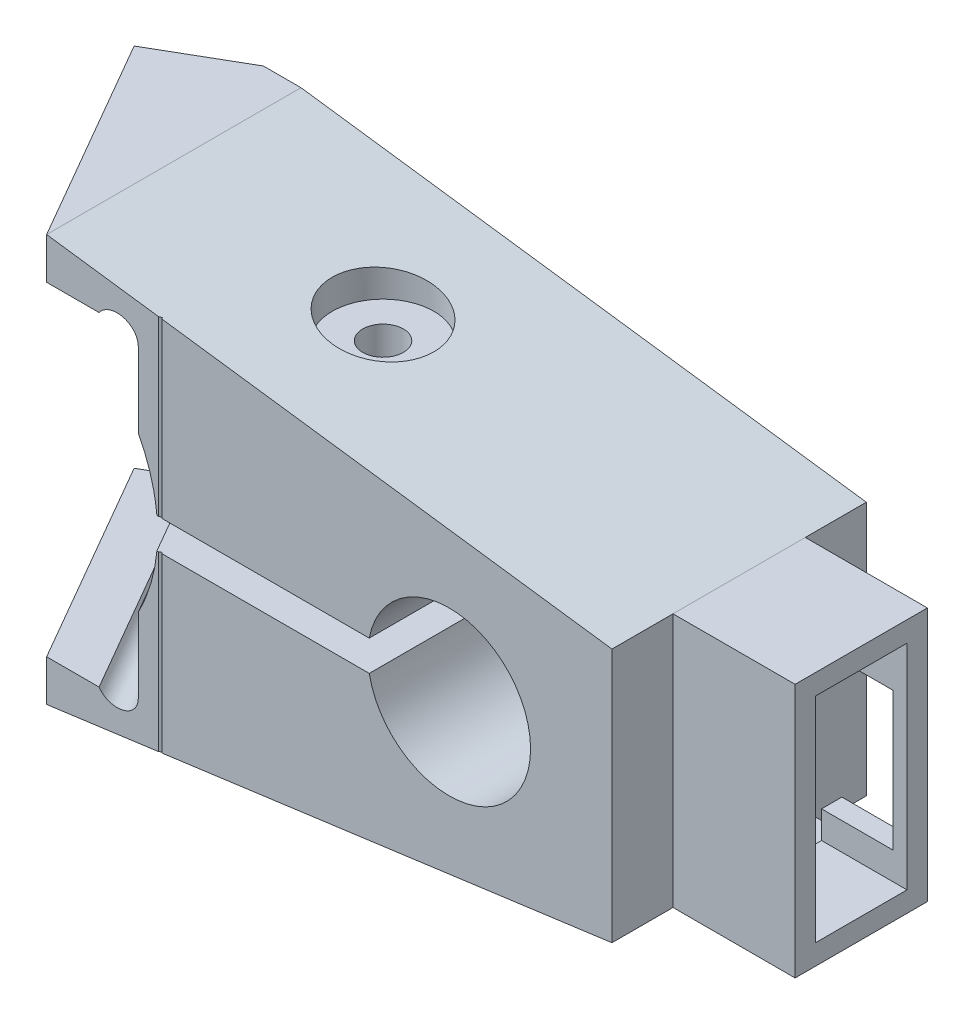
SolidWorks part; units mm, degrees
material "ABS"
ref_plane "Front Plane" through (0, 0, 0) normal (0, 0, 1) x (1, 0, 0)
ref_plane "Top Plane" through (0, 0, 0) normal (0, 1, 0) x (1, 0, 0)
ref_plane "Right Plane" through (0, 0, 0) normal (1, 0, 0) x (0, 0, -1)
sketch "Sketch1" plane through (0, 0, 0) normal (0, 1, 0) x (1, 0, 0)
  line L0 (-35, 12.5) -> (-20.5662, -12.5)
  line L1 (-20.5662, -12.5) -> (35, -12.5)
  line L2 (-27.7831, 0) -> (-41.077, -7.6752) construction
  line L3 (-35, 12.5) -> (35, 12.5)
  line L4 (35, -12.5) -> (35, 12.5)
  line L5 (-23.0337, -8.2263) -> (35, 12.5) construction
  line L6 (-35, 12.5) -> (35, -12.5) construction
  point P0 (0, 0)
  dimension "D1" = 70
  dimension "D2" = 25
  dimension "D3" = 120
extrude "Boss-Extrude1" add sketch "Sketch1" along normal blind 40
sketch "Sketch2" plane through (0, 0, 12.5) normal (0, 0, 1) x (1, 0, 0)
  line L0 (-20.5662, 40) -> (35, 32.5)
  line L1 (35, 40) -> (35, 0) construction
  line L3 (35, 7.5) -> (-20.5662, 0)
  line L4 (-20.5662, 0) -> (35, 0)
  line L5 (35, 0) -> (35, 7.5)
  line L6 (35, 32.5) -> (35, 40)
  line L7 (35, 40) -> (-20.5662, 40)
  dimension "D1" = 25
  dimension "D2" = 7.5
  dimension "D3" = 7.5
  dimension "D4" = 97.687
  dimension "D5" = 97.687
extrude "Cut-Extrude1" cut sketch "Sketch2" against normal blind 40
sketch "Sketch3" plane through (-20.8373, 0, 12.0304) normal (-0.866, 0, 0.5) x (0.5, 0, 0.866)
  line L1 (-12.8642, 25.3819) -> (-8.4874, 25.3819)
  line L2 (-12.8642, 25.3819) -> (-12.8642, 17.4606)
  line L3 (-12.8642, 17.4606) -> (-8.4874, 17.4606)
  line L4 (-8.4874, 25.3819) -> (-8.4874, 17.4606)
  line L5 (-12.8642, 25.3819) -> (-8.4874, 17.4606) construction
  line L6 (-12.8642, 17.4606) -> (-8.4874, 25.3819) construction
  point P0 (-10.6758, 21.4213)
extrude "Boss-Extrude2" add sketch "Sketch3" along normal blind 40
sketch "Sketch4" plane through (-4.2437, 0, -7.3503) normal (0.5, 0, 0.866) x (0.866, 0, -0.5)
  line L0 (-25.2609, 35.9341) -> (-19.5976, 35.9341)
  line L1 (-52.0609, 0.9968) -> (-14.0609, 0.9968) construction
  line L2 (-52.0609, 0.9968) -> (-52.0609, 38.9968) construction
  line L3 (-52.0609, 38.9968) -> (-14.0609, 38.9968) construction
  line L4 (-14.0609, 0.9968) -> (-14.0609, 38.9968) construction
  line L5 (-52.0609, 0.9968) -> (-20.0148, 33.0429) construction
  line L6 (-52.0609, 38.9968) -> (-14.0609, 0.9968) construction
  line L7 (-24.0609, 40) -> (-24.0609, 0) construction
  line L8 (-16.2609, 34.9968) -> (-16.2609, 27.6232)
  line L9 (-16.7881, 36.2696) -> (-14.0609, 38.9968) construction
  line L10 (-69.3542, 19.9968) -> (-7.4274, 19.9968) construction
  line L11 (-16.2609, 4.9968) -> (-16.2609, 12.3703)
  line L12 (-25.2609, 4.0594) -> (-19.5976, 4.0594)
  line L13 (-25.2609, 35.9341) -> (-25.2609, 26.6131)
  line L14 (-25.2609, 26.6131) -> (-69.3542, 27.5468)
  line L15 (-69.3542, 27.5468) -> (-69.3542, 11.5496)
  line L16 (-69.3542, 11.5496) -> (-25.2609, 11.5496)
  line L17 (-25.2609, 11.5496) -> (-25.2609, 4.0594)
  arc A0 (-16.2609, 34.9968) -> (-19.5976, 35.9341) centre (-18.0609, 34.9968) ccw
  arc A1 (-16.2609, 4.9968) -> (-19.5976, 4.0594) centre (-18.0609, 4.9968) cw
  arc A2 (-16.2609, 12.3703) -> (-16.2609, 27.6232) centre (-33.0609, 19.9968) ccw
  point P0 (-33.0609, 19.9968)
  dimension "D4" = 3.6
  dimension "D5" = 5.6633
  dimension "D8" = 36.9
  dimension "D1" = 38
  dimension "D2" = 38
  dimension "D3" = 10
  dimension "D6" = 4
  dimension "D7" = 9
extrude "Cut-Extrude2" cut sketch "Sketch4" against normal through all both and the other way through all
sketch "Sketch5" plane through (0, 0, -12.5) normal (0, 0, -1) x (-1, 0, 0)
  line L0 (-35, 32.5) -> (-35, 7.5) construction
  line L1 (35, 40) -> (20.5662, 40) construction
  line L2 (-11.1413, 21.5) -> (29.8749, 21.5)
  line L3 (29.8749, 21.5) -> (29.8749, 18.5)
  line L4 (29.8749, 18.5) -> (-11.1425, 18.5)
  arc A0 (-11.1413, 21.5) -> (-11.1425, 18.5) centre (-19, 20.0032) ccw
  point P1 (-35, 20)
  dimension "D1" = 16
  dimension "D2" = 16
  dimension "D3" = 3
  dimension "D4" = 1.5
  dimension "D5" = 18.5
  dimension "D6" = 18.5
extrude "Cut-Extrude3" cut sketch "Sketch5" against normal blind 40
sketch "Sketch6" plane through (0, 18.5, 0) normal (0, 1, 0) x (1, 0, 0)
  circle A0 centre (0, 0) radius 2
  dimension "D1" = 4
extrude "Cut-Extrude4" cut sketch "Sketch6" against normal through all both and the other way through all
sketch "Sketch7" plane through (0, 0, 0) normal (0, -1, 0) x (1, 0, 0)
  line L1 (1.8526, 3.4614) -> (-2.0714, 3.3351)
  line L2 (-2.0714, 3.3351) -> (-3.9239, -0.1263)
  line L3 (-3.9239, -0.1263) -> (-1.8526, -3.4614)
  line L4 (-1.8526, -3.4614) -> (2.0714, -3.3351)
  line L5 (2.0714, -3.3351) -> (3.9239, 0.1263)
  line L6 (3.9239, 0.1263) -> (1.8526, 3.4614)
  circle A0 centre (0, 0) radius 3.4 construction
  dimension "D1" = 6.8
extrude "Cut-Extrude5" cut sketch "Sketch7" against normal blind 5
sketch "Sketch8" plane through (0, 40, 0) normal (0, 1, 0) x (1, 0, 0)
  circle A0 centre (0, 0) radius 5
  dimension "D1" = 10
extrude "Cut-Extrude6" cut sketch "Sketch8" against normal blind 5
sketch "Sketch9" plane through (-14.0823, 0, 8.1304) normal (-0.866, 0, 0.5) x (0.5, 0, 0.866)
  line L0 (-28.3253, 40) -> (0.5422, 40) construction
  line L1 (6.0455, 1) -> (-22.9545, 1) construction
  line L2 (6.0455, 1) -> (6.0455, 39) construction
  line L3 (6.0455, 39) -> (-22.9545, 39) construction
  line L4 (-22.9545, 1) -> (-22.9545, 39) construction
  line L5 (6.0455, 1) -> (-22.9545, 39) construction
  line L6 (6.0455, 39) -> (-22.9545, 1) construction
  line L7 (5.0455, 34.9968) -> (5.0455, 27.6232) construction
  line L8 (-22.9545, 45.7496) -> (-22.9545, -7.6537)
  line L9 (-22.9545, -7.6537) -> (-29.1772, -7.6537)
  line L10 (-29.1772, -7.6537) -> (-29.1772, 45.7496)
  line L11 (-29.1772, 45.7496) -> (-22.9545, 45.7496)
  line L12 (6.0455, 45.7496) -> (6.0455, -7.6537)
  line L13 (6.0455, -7.6537) -> (13.7172, -7.6537)
  line L14 (13.7172, -7.6537) -> (13.7172, 42.6866)
  line L15 (13.7172, 42.6866) -> (13.7172, 45.7496)
  line L16 (13.7172, 45.7496) -> (6.0455, 45.7496)
  point P0 (-8.4545, 20)
  dimension "D1" = 38
  dimension "D2" = 1
  dimension "D3" = 29
  dimension "D4" = 1
extrude "Cut-Extrude7" cut sketch "Sketch9" along direction (0.866, 0, -0.5) on the side of the normal blind 16 from offset 2 offset against normal yes
sketch "Sketch10" plane through (35, 0, 0) normal (1, 0, 0) x (0, 0, -1)
  line L0 (-12.5, 32.5) -> (-12.5, 7.5) construction
  line L1 (6.5, 7.5) -> (-6.5, 7.5)
  line L2 (6.5, 7.5) -> (6.5, 32.5)
  line L3 (6.5, 32.5) -> (-6.5, 32.5)
  line L4 (-6.5, 7.5) -> (-6.5, 32.5)
  line L5 (4.5, 9.5) -> (-4.5, 9.5)
  line L6 (4.5, 9.5) -> (4.5, 30.5)
  line L7 (4.5, 30.5) -> (-4.5, 30.5)
  line L8 (-4.5, 9.5) -> (-4.5, 30.5)
  line L9 (12.5, 32.5) -> (12.5, 7.5) construction
  line L10 (12.5, 7.5) -> (-12.5, 7.5) construction
  dimension "D1" = 2
  dimension "D2" = 2
  dimension "D3" = 2
  dimension "D4" = 2
  dimension "D5" = 6
  dimension "D6" = 6
  dimension "D7" = 9
  dimension "D8" = 21
  dimension "D9" = 0
extrude "Boss-Extrude3" add sketch "Sketch10" along normal blind 12
sketch "Sketch11" plane through (0, 0, -6.5) normal (0, 0, -1) x (-1, 0, 0)
  line L1 (-35, 7.5) -> (-35, 32.5) construction
  line L2 (-38.6, 30.8) -> (-35, 30.8)
  line L3 (-35, 30.8) -> (-35, 25.8)
  line L4 (-38.6, 9.2) -> (-38.6, 12.2)
  line L5 (-38.6, 12.2) -> (-45.6, 12.2)
  line L6 (-38.6, 9.2) -> (-35, 9.2)
  line L7 (-38.6, 25.8) -> (-45.6, 25.8)
  line L8 (-45.6, 12.2) -> (-45.6, 25.8)
  line L9 (-47, 7.5) -> (-35, 7.5) construction
  line L11 (-38.6, 25.8) -> (-38.6, 30.8)
  line L12 (-35, 9.2) -> (-35, 12.2)
  line L15 (-35, 12.2) -> (-35, 25.8)
  dimension "D2" = 0
  dimension "D3" = 3
  dimension "D4" = 10.6
  dimension "D5" = 13.6
  dimension "D6" = 5
  dimension "D7" = 1.7
  dimension "D8" = 3.6
  dimension "D10" = 13.6
extrude "Cut-Extrude8" cut sketch "Sketch11" against normal blind 11
